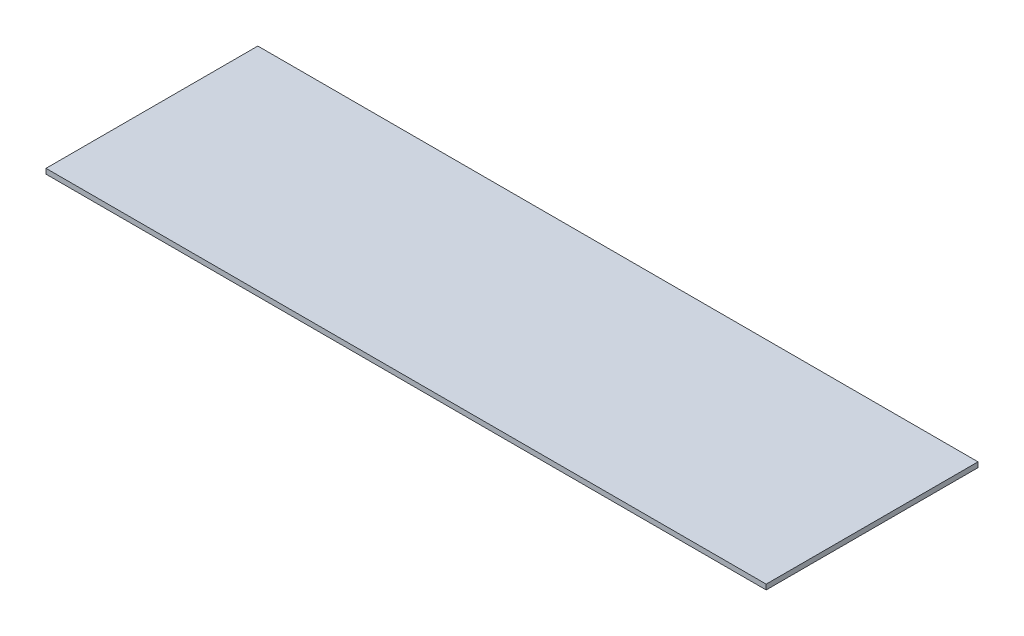
SolidWorks part; units mm, degrees
ref_plane "Front Plane" through (0, 0, 0) normal (0, 0, 1) x (1, 0, 0)
ref_plane "Top Plane" through (0, 0, 0) normal (0, 1, 0) x (1, 0, 0)
ref_plane "Right Plane" through (0, 0, 0) normal (1, 0, 0) x (0, 0, -1)
sketch "Sketch1" plane through (0, 0, 0) normal (0, 1, 0) x (1, 0, 0)
  line L1 (850, -250) -> (-850, -250)
  line L2 (850, -250) -> (850, 250)
  line L3 (850, 250) -> (-850, 250)
  line L4 (-850, -250) -> (-850, 250)
  line L5 (850, -250) -> (-850, 250) construction
  line L6 (850, 250) -> (-850, -250) construction
  point P0 (0, 0)
  dimension "D1" = 500
  dimension "D2" = 1700
extrude "Boss-Extrude1" add sketch "Sketch1" along normal blind 12
